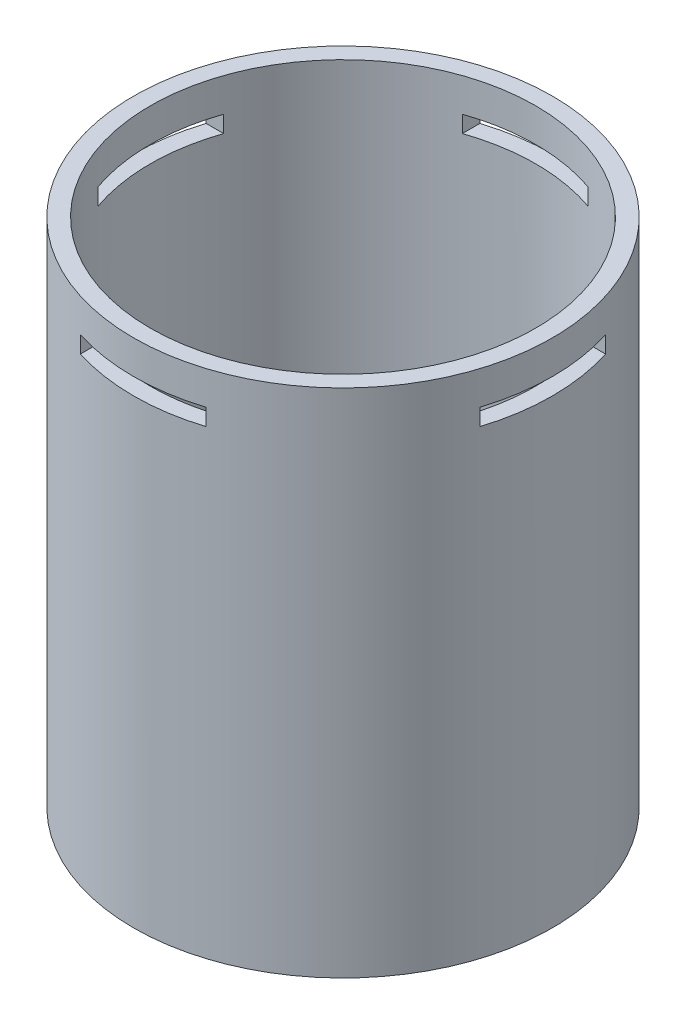
SolidWorks part; units mm, degrees
ref_plane "Front Plane" through (0, 0, 0) normal (0, 0, 1) x (1, 0, 0)
ref_plane "Top Plane" through (0, 0, 0) normal (0, 1, 0) x (1, 0, 0)
ref_plane "Right Plane" through (0, 0, 0) normal (1, 0, 0) x (0, 0, -1)
sketch "Sketch1" plane through (0, 0, 0) normal (0, 1, 0) x (1, 0, 0)
  circle A0 centre (0, 0) radius 25
  circle A1 centre (0, 0) radius 23
  dimension "D1" = 50
  dimension "D2" = 46
extrude "Boss-Extrude1" add sketch "Sketch1" along normal blind 61
sketch "Sketch2" plane through (0, 0, 0) normal (0, 0, 1) x (1, 0, 0)
  line L1 (7.5, 57) -> (-7.5, 57)
  line L2 (7.5, 57) -> (7.5, 55)
  line L3 (7.5, 55) -> (-7.5, 55)
  line L4 (-7.5, 57) -> (-7.5, 55)
  point P4 (0, 55)
  dimension "D1" = 2
  dimension "D2" = 15
  dimension "D3" = 55
extrude "Cut-Extrude2" cut sketch "Sketch2" against normal blind 26
pattern_circular "CirPattern1" count 4 over 360 about axis through (0, 0, 0) along (0, 1, 0) of "Cut-Extrude2"
